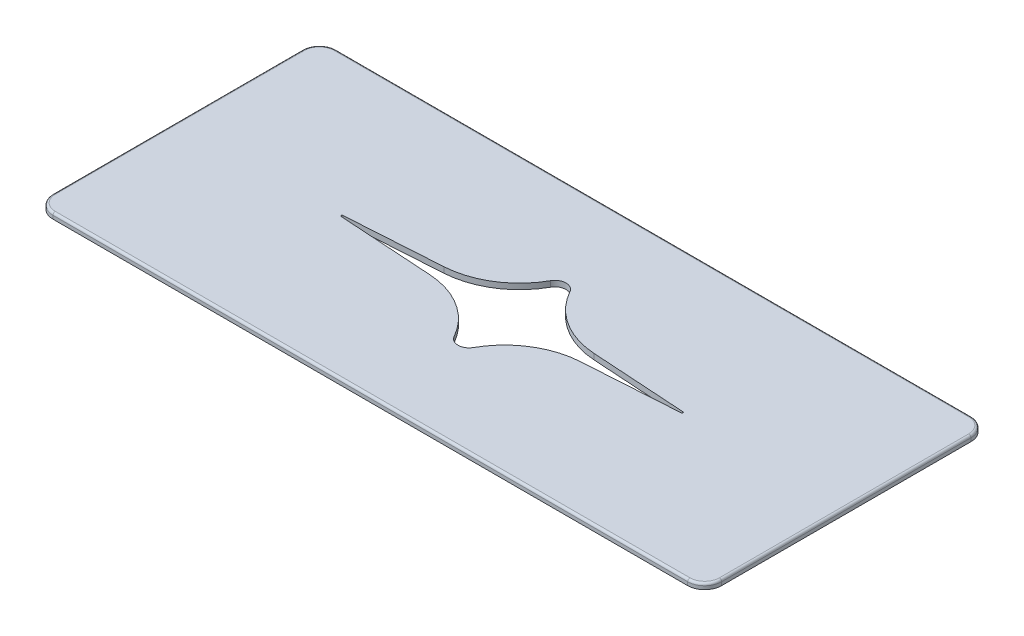
SolidWorks part; units mm, degrees
material "201 Annealed Stainless Steel (SS)"
ref_plane "Front Plane" through (0, 0, 0) normal (0, 0, 1) x (1, 0, 0)
ref_plane "Top Plane" through (0, 0, 0) normal (0, 1, 0) x (1, 0, 0)
ref_plane "Right Plane" through (0, 0, 0) normal (1, 0, 0) x (0, 0, -1)
sketch "Sketch1" plane through (0, 0, 0) normal (0, 1, 0) x (1, 0, 0)
  line L1 (-147.5, 62.5) -> (147.5, 62.5)
  line L2 (-147.5, 62.5) -> (-147.5, -62.5)
  line L3 (-147.5, -62.5) -> (147.5, -62.5)
  line L4 (147.5, 62.5) -> (147.5, -62.5)
  line L5 (-147.5, 62.5) -> (147.5, -62.5) construction
  line L6 (-147.5, -62.5) -> (147.5, 62.5) construction
  point P0 (0, 0)
  dimension "D1" = 295
  dimension "D2" = 125
extrude "Boss-Extrude1" add sketch "Sketch1" along normal blind 2.5
fillet "Fillet1" radius 7.5 4 edges at (147.5, 1.25, 62.5) (-147.5, 1.25, 62.5) (147.5, 1.25, -62.5) (-147.5, 1.25, -62.5)
fillet "Fillet2" radius 1 8 edges at (145.3033, 2.5, -60.3033) (147.5, 2.5, 0) (145.3033, 2.5, 60.3033) (0, 2.5, 62.5) (-145.3033, 2.5, 60.3033) (-147.5, 2.5, 0) (-145.3033, 2.5, -60.3033) (0, 2.5, -62.5)
sketch "Sketch4" plane through (0, 2.5, 0) normal (0, 1, 0) x (1, 0, 0)
  line L0 (-75.0254, 0.3951) -> (-33.074, 3.09)
  line L1 (-75, 0) -> (75, 0) construction
  line L2 (-75, 1.25) -> (75, 1.25) construction
  line L3 (-75, -1.25) -> (75, -1.25) construction
  line L4 (0, 34.3443) -> (0, 0) construction
  line L5 (75.0254, 0.3951) -> (33.074, 3.09)
  line L6 (-23.8422, 0) -> (49433.0468, 0) construction
  line L7 (-75.0254, -0.3951) -> (-33.074, -3.09)
  line L8 (75.0254, -0.3951) -> (33.074, -3.09)
  arc A0 (-75, 1.25) -> (-75, -1.25) centre (-75, 0) ccw construction
  arc A1 (75, -1.25) -> (75, 1.25) centre (75, 0) ccw construction
  circle A2 centre (-75, 0) radius 0.3959
  arc A3 (-33.074, 3.09) -> (0, 34.3443) centre (-35.3573, 38.6332) ccw
  circle A4 centre (75, 0) radius 0.3959
  arc A5 (33.074, 3.09) -> (0, 34.3443) centre (35.3573, 38.6332) cw
  arc A6 (-33.074, -3.09) -> (0, -34.3443) centre (-35.3573, -38.6332) cw
  arc A7 (33.074, -3.09) -> (0, -34.3443) centre (35.3573, -38.6332) ccw
  arc A8 (-4.2367, 21.3115) -> (4.2367, 21.3115) centre (0, 18.9533) cw
  arc A9 (-4.2367, -21.3115) -> (4.2367, -21.3115) centre (0, -18.9533) ccw
  point P4 (0, 0)
  point P6 (0, 0)
  dimension "D1" = 150
  dimension "D2" = 2.5
extrude "Cut-Extrude4" cut sketch "Sketch4" against normal blind 10 contours A6 A9 A7 L8 A4 L5 A5 A8 A3 L0 A2 L7
sketch "Sketch3" plane through (0, 2.5, 0) normal (0, 1, 0) x (1, 0, 0)
  line L1 (-110, -25) -> (110, -25) construction
  line L2 (-110, -25) -> (-110, 25) construction
  line L3 (-110, 25) -> (110, 25) construction
  line L4 (110, -25) -> (110, 25) construction
  text T0 "LUNAR" font "Century Gothic" height 50
  point P4 (-110, 0)
  point P6 (0, 25)
  dimension "D1" = 220
  dimension "D2" = 50
extrude "Cut-Extrude3" [suppressed] cut sketch "Sketch3" against normal blind 0.5
